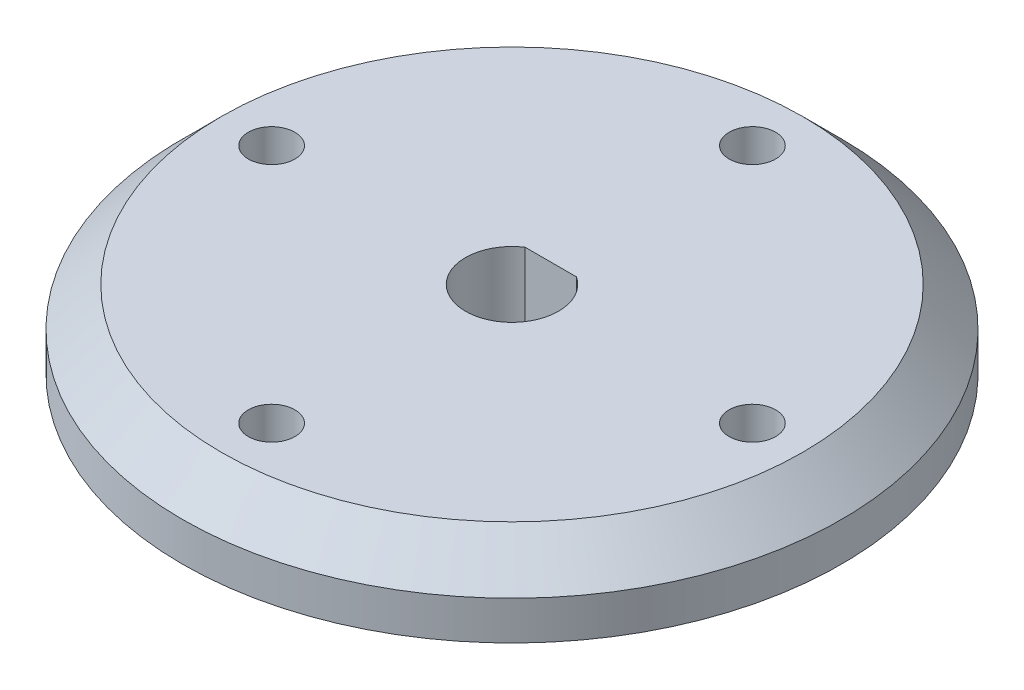
SolidWorks part; units mm, degrees
ref_plane "Front Plane" through (0, 0, 0) normal (0, 0, 1) x (1, 0, 0)
ref_plane "Top Plane" through (0, 0, 0) normal (0, 1, 0) x (1, 0, 0)
ref_plane "Right Plane" through (0, 0, 0) normal (1, 0, 0) x (0, 0, -1)
sketch "Sketch1" plane through (0, 0, 0) normal (0, 1, 0) x (1, 0, 0)
  line L0 (-1.6583, 2.5) -> (1.6583, 2.5)
  circle A0 centre (0, 0) radius 21.25
  circle A1 centre (0, 0) radius 15.5 construction
  circle A2 centre (0, 0) radius 3 construction
  circle A3 centre (0, 15.5) radius 1.5
  circle A4 centre (15.5, 0) radius 1.5
  circle A5 centre (0, -15.5) radius 1.5
  circle A6 centre (-15.5, 0) radius 1.5
  arc A7 (-1.6583, 2.5) -> (1.6583, 2.5) centre (0, 0) ccw
  dimension "D1" = 6
  dimension "D2" = 31
  dimension "D3" = 42.5
  dimension "D4" = 3
  dimension "D5" = 2.5
extrude "Boss-Extrude1" add sketch "Sketch1" along normal blind 5
chamfer "Chamfer1" distance 2.5 angle 45 1 edges at (0, 5, 21.25)
